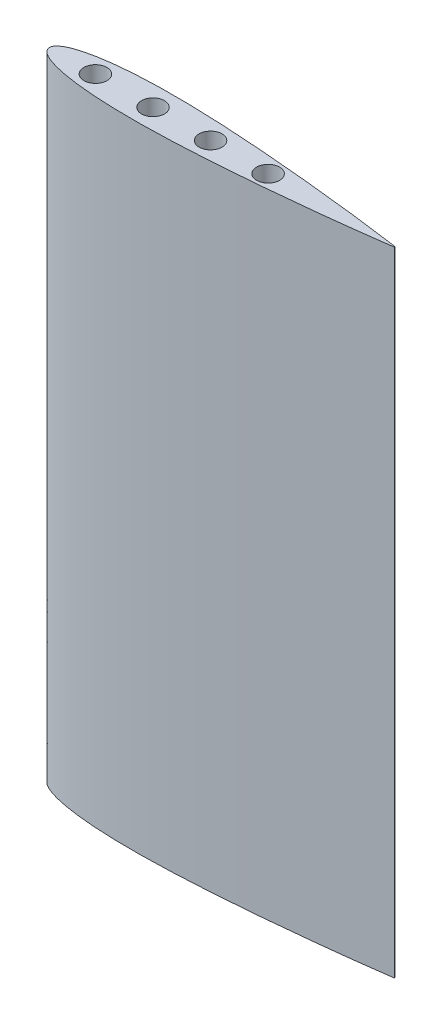
SolidWorks part; units mm, degrees
material "ABS"
ref_plane "Front Plane" through (0, 0, 0) normal (0, 0, 1) x (1, 0, 0)
ref_plane "Top Plane" through (0, 0, 0) normal (0, 1, 0) x (1, 0, 0)
ref_plane "Right Plane" through (0, 0, 0) normal (1, 0, 0) x (0, 0, -1)
curve "Curve1"
  spline degree 3 poles (25.4, 0, 0.032) (25.3951, 0, 0.0327) (25.3753, 0, 0.0355) (25.3309, 0, 0.0417) (25.257, 0, 0.052) (25.1537, 0, 0.0664) (25.0214, 0, 0.0846) (24.8603, 0, 0.1068) (24.6708, 0, 0.1326) (24.4533, 0, 0.1619) (24.2084, 0, 0.1946) (23.9366, 0, 0.2304) (23.6385, 0, 0.2691) (23.3149, 0, 0.3106) (22.9666, 0, 0.3545) (22.5942, 0, 0.4008) (22.1987, 0, 0.449) (21.7811, 0, 0.499) (21.3422, 0, 0.5505) (20.8832, 0, 0.6032) (20.405, 0, 0.6571) (19.9089, 0, 0.7116) (19.3959, 0, 0.7667) (18.8673, 0, 0.8219) (18.3242, 0, 0.8772) (17.7681, 0, 0.9321) (17.2001, 0, 0.9864) (16.6216, 0, 1.0399) (16.0339, 0, 1.0922) (15.4384, 0, 1.143) (14.8366, 0, 1.1921) (14.2297, 0, 1.2391) (13.6193, 0, 1.2836) (13.0067, 0, 1.3254) (12.3935, 0, 1.3642) (11.7809, 0, 1.3995) (11.1705, 0, 1.4311) (10.5636, 0, 1.4587) (9.9618, 0, 1.4818) (9.3663, 0, 1.5004) (8.7786, 0, 1.514) (8.2001, 0, 1.5224) (7.632, 0, 1.5254) (7.0758, 0, 1.5227) (6.5327, 0, 1.5144) (6.0041, 0, 1.5) (5.491, 0, 1.4798) (4.9948, 0, 1.4535) (4.5166, 0, 1.4212) (4.0575, 0, 1.3829) (3.6185, 0, 1.3388) (3.2008, 0, 1.2888) (2.8052, 0, 1.2334) (2.4327, 0, 1.1725) (2.0841, 0, 1.1064) (1.7603, 0, 1.0355) (1.462, 0, 0.96) (1.1898, 0, 0.8801) (0.9445, 0, 0.7962) (0.7264, 0, 0.7086) (0.536, 0, 0.6175) (0.3737, 0, 0.523) (0.2396, 0, 0.4254) (0.1341, 0, 0.3245) (0.0574, 0, 0.22) (0.0105, 0, 0.1114) (-0.0051, 0, 0) (0.0105, 0, -0.1114) (0.0574, 0, -0.22) (0.1341, 0, -0.3245) (0.2396, 0, -0.4254) (0.3737, 0, -0.523) (0.536, 0, -0.6175) (0.7264, 0, -0.7086) (0.9445, 0, -0.7962) (1.1898, 0, -0.8801) (1.462, 0, -0.96) (1.7603, 0, -1.0355) (2.0841, 0, -1.1064) (2.4327, 0, -1.1725) (2.8052, 0, -1.2334) (3.2008, 0, -1.2888) (3.6185, 0, -1.3388) (4.0575, 0, -1.3829) (4.5166, 0, -1.4212) (4.9948, 0, -1.4535) (5.491, 0, -1.4798) (6.0041, 0, -1.5) (6.5327, 0, -1.5144) (7.0758, 0, -1.5227) (7.632, 0, -1.5254) (8.2001, 0, -1.5224) (8.7786, 0, -1.514) (9.3663, 0, -1.5004) (9.9618, 0, -1.4818) (10.5636, 0, -1.4587) (11.1705, 0, -1.4311) (11.7809, 0, -1.3995) (12.3935, 0, -1.3642) (13.0067, 0, -1.3254) (13.6193, 0, -1.2836) (14.2297, 0, -1.2391) (14.8366, 0, -1.1921) (15.4384, 0, -1.143) (16.0339, 0, -1.0922) (16.6216, 0, -1.0399) (17.2001, 0, -0.9864) (17.7681, 0, -0.9321) (18.3242, 0, -0.8772) (18.8673, 0, -0.8219) (19.3959, 0, -0.7667) (19.9089, 0, -0.7116) (20.405, 0, -0.6571) (20.8832, 0, -0.6032) (21.3422, 0, -0.5505) (21.7811, 0, -0.499) (22.1987, 0, -0.449) (22.5942, 0, -0.4008) (22.9666, 0, -0.3545) (23.3149, 0, -0.3106) (23.6385, 0, -0.2691) (23.9366, 0, -0.2304) (24.2084, 0, -0.1946) (24.4533, 0, -0.1619) (24.6708, 0, -0.1326) (24.8603, 0, -0.1068) (25.0214, 0, -0.0846) (25.1537, 0, -0.0664) (25.257, 0, -0.052) (25.3309, 0, -0.0417) (25.3753, 0, -0.0355) (25.3951, 0, -0.0327) (25.4, 0, -0.032) knots 0 0 0 0 0.000289 0.001156 0.002598 0.004612 0.007194 0.010336 0.014031 0.018272 0.023046 0.028343 0.03415 0.040454 0.047238 0.054489 0.062187 0.070314 0.078852 0.08778 0.097078 0.106722 0.116691 0.126961 0.137507 0.148306 0.159331 0.170556 0.181957 0.193504 0.205171 0.216932 0.228758 0.240621 0.252495 0.26435 0.276161 0.287898 0.299536 0.311047 0.322405 0.333584 0.344559 0.355306 0.3658 0.376018 0.385937 0.395538 0.404798 0.413699 0.422221 0.430349 0.438066 0.445357 0.452209 0.458612 0.464554 0.47003 0.475035 0.479569 0.483637 0.48725 0.490431 0.493219 0.495674 0.497891 0.5 0.502109 0.504326 0.506781 0.509569 0.51275 0.516363 0.520431 0.524965 0.52997 0.535446 0.541388 0.547791 0.554643 0.561934 0.569651 0.577779 0.586301 0.595202 0.604462 0.614063 0.623982 0.6342 0.644694 0.655441 0.666416 0.677595 0.688953 0.700464 0.712102 0.723839 0.73565 0.747505 0.759379 0.771242 0.783068 0.794829 0.806496 0.818043 0.829444 0.840669 0.851694 0.862493 0.873039 0.883309 0.893278 0.902922 0.91222 0.921148 0.929686 0.937813 0.945511 0.952762 0.959546 0.96585 0.971657 0.976954 0.981728 0.985969 0.989664 0.992806 0.995388 0.997402 0.998844 0.999711 1 1 1 1
sketch "Sketch4" plane through (0, 0, 0) normal (0, 1, 0) x (1, 0, 0)
  line L0 (38.1, 0.048) -> (38.1, -0.048)
  line L1 (0, 0) -> (38.1, 0) construction
  spline S1 degree 3 poles (38.1, -0.048) (38.0926, -0.049) (38.0629, -0.0532) (37.9446, -0.0698) (37.7676, -0.0945) (37.5321, -0.127) (37.2904, -0.1602) (37.0061, -0.1989) (36.6799, -0.2429) (36.3125, -0.2919) (35.9049, -0.3456) (35.4578, -0.4037) (34.9724, -0.4659) (34.2521, -0.5568) (33.4845, -0.6511) (32.6716, -0.7484) (32.0134, -0.8257) (31.3248, -0.9049) (30.6075, -0.9856) (29.8633, -1.0674) (29.0938, -1.15) (28.3009, -1.2328) (27.4864, -1.3157) (26.6521, -1.3981) (25.8001, -1.4797) (24.9323, -1.5598) (24.0508, -1.6383) (23.1576, -1.7146) (22.2549, -1.7882) (21.3446, -1.8586) (20.429, -1.9254) (19.5101, -1.9882) (18.5902, -2.0463) (17.3679, -2.1168) (16.1511, -2.1762) (14.6487, -2.2341) (13.466, -2.2666) (12.3001, -2.2836) (11.448, -2.288) (10.6137, -2.2841) (9.7991, -2.2716) (9.0061, -2.2501) (8.2366, -2.2197) (7.4922, -2.1802) (6.7749, -2.1318) (6.0862, -2.0744) (5.4278, -2.0081) (4.8012, -1.9332) (4.2078, -1.8501) (3.649, -1.7587) (3.1262, -1.6597) (2.6405, -1.5533) (2.193, -1.44) (1.7848, -1.3202) (1.4167, -1.1944) (1.0895, -1.0629) (0.804, -0.9262) (0.5605, -0.7845) (0.3594, -0.6381) (0.2012, -0.4868) (0.0861, -0.33) (0.0157, -0.1671) (-0.0077, 0) (0.0157, 0.1671) (0.0861, 0.33) (0.2012, 0.4868) (0.3594, 0.6381) (0.5605, 0.7845) (0.804, 0.9262) (1.0895, 1.0629) (1.4167, 1.1944) (1.7848, 1.3202) (2.193, 1.44) (2.6405, 1.5533) (3.1262, 1.6597) (3.649, 1.7587) (4.2078, 1.8501) (4.8012, 1.9332) (5.4278, 2.0081) (6.0862, 2.0744) (6.7749, 2.1318) (7.4922, 2.1802) (8.2366, 2.2197) (9.0061, 2.2501) (9.7991, 2.2716) (10.6137, 2.2841) (11.448, 2.288) (12.3001, 2.2836) (13.466, 2.2666) (14.9526, 2.2257) (16.4547, 2.1623) (17.6713, 2.0993) (18.5902, 2.0463) (19.5101, 1.9882) (20.429, 1.9254) (21.3446, 1.8586) (22.2549, 1.7882) (23.1576, 1.7146) (24.0508, 1.6383) (24.9323, 1.5598) (25.8001, 1.4797) (26.6521, 1.3981) (27.4864, 1.3157) (28.3009, 1.2328) (29.0938, 1.15) (29.8633, 1.0674) (30.6075, 0.9856) (31.3248, 0.9049) (32.0134, 0.8257) (32.6716, 0.7484) (33.4845, 0.6511) (34.2521, 0.5568) (34.9724, 0.4659) (35.4578, 0.4037) (35.9049, 0.3456) (36.3125, 0.2919) (36.6799, 0.2429) (37.0061, 0.1989) (37.2904, 0.1602) (37.5321, 0.127) (37.7676, 0.0945) (37.9446, 0.0698) (38.0629, 0.0532) (38.0926, 0.049) (38.1, 0.048) knots 0 0 0 0 0.000289 0.001156 0.004612 0.007194 0.010336 0.014031 0.018272 0.023046 0.028343 0.03415 0.040454 0.047238 0.062187 0.070314 0.078852 0.08778 0.097078 0.106722 0.116691 0.126961 0.137507 0.148306 0.159331 0.170556 0.181957 0.193504 0.205171 0.216932 0.228758 0.240621 0.252495 0.26435 0.287898 0.299536 0.322405 0.333584 0.344559 0.355306 0.3658 0.376018 0.385937 0.395538 0.404798 0.413699 0.422221 0.430349 0.438066 0.445357 0.452209 0.458612 0.464554 0.47003 0.475035 0.479569 0.483637 0.48725 0.490431 0.493219 0.495674 0.497891 0.5 0.502109 0.504326 0.506781 0.509569 0.51275 0.516363 0.520431 0.524965 0.52997 0.535446 0.541388 0.547791 0.554643 0.561934 0.569651 0.577779 0.586301 0.595202 0.604462 0.614063 0.623982 0.6342 0.644694 0.655441 0.666416 0.677595 0.700464 0.723839 0.73565 0.747505 0.759379 0.771242 0.783068 0.794829 0.806496 0.818043 0.829444 0.840669 0.851694 0.862493 0.873039 0.883309 0.893278 0.902922 0.91222 0.921148 0.929686 0.937813 0.952762 0.959546 0.96585 0.971657 0.976954 0.981728 0.985969 0.989664 0.992806 0.995388 0.998844 0.999711 1 1 1 1
  dimension "D1" = 38.1
extrude "Boss-Extrude1" add sketch "Sketch4" along normal blind 69.85
sketch "Sketch5" plane through (0, 69.85, 0) normal (0, 1, 0) x (1, 0, 0)
  circle A0 centre (5.08, 0) radius 1.27
  circle A1 centre (11.43, 0) radius 1.27
  circle A2 centre (17.78, 0) radius 1.27
  circle A3 centre (24.13, 0) radius 1.27
  dimension "D1" = 2.54
  dimension "D2" = 6.35
  dimension "D3" = 12.7
  dimension "D4" = 19.05
  dimension "D5" = 5.08
extrude "Cut-Extrude1" cut sketch "Sketch5" against normal blind 12.7
